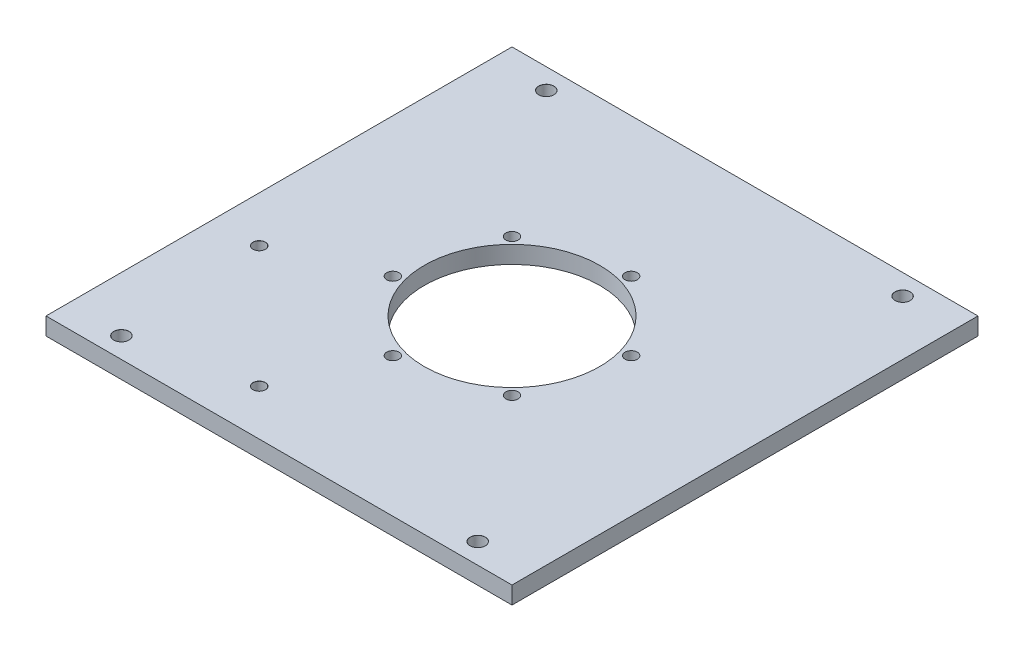
SolidWorks part; units mm, degrees
material "6061 Alloy"
ref_plane "Front Plane" through (0, 0, 0) normal (0, 0, 1) x (1, 0, 0)
ref_plane "Top Plane" through (0, 0, 0) normal (0, 1, 0) x (1, 0, 0)
ref_plane "Right Plane" through (0, 0, 0) normal (1, 0, 0) x (0, 0, -1)
sketch "Sketch1" plane through (0, 0, 0) normal (0, 1, 0) x (1, 0, 0)
  line L1 (-85, -85) -> (85, -85)
  line L2 (-85, -85) -> (-85, 85)
  line L3 (-85, 85) -> (85, 85)
  line L4 (85, -85) -> (85, 85)
  line L5 (-85, -85) -> (85, 85) construction
  line L6 (-85, 85) -> (85, -85) construction
  circle A1 centre (0, 0) radius 39.5
  arc A5 (-25.1023, 25.1023) -> (9.1881, 34.2904) centre (0, 0) cw
  arc A7 (9.1881, 34.2904) -> (-34.2904, -9.1881) centre (0, 0) ccw
  arc A9 (-34.2904, -9.1881) -> (-9.1881, -34.2904) centre (0, 0) ccw
  arc A11 (-9.1881, -34.2904) -> (25.1023, -25.1023) centre (0, 0) ccw
  circle A13 centre (0, 0) radius 32
  arc A14 (25.1023, -25.1023) -> (34.2904, 9.1881) centre (0, 0) ccw
extrude "Boss-Extrude3" add sketch "Sketch1" along normal blind 6.35
hole_wizard "M4 Clearance Hole2" positions "Sketch6" profile "Sketch7" hole size "M4" standard "ANSI Metric" end condition through all
sketch "Sketch6" plane through (0, 0, 0) normal (0, -1, 0) x (-1, 0, 0)
  point P0 (-9.1881, 34.2904)
  point P3 (25.1023, 25.1023)
  point P6 (34.2904, -9.1881)
  point P9 (9.1881, -34.2904)
  point P12 (-25.1023, -25.1023)
  point P15 (-34.2904, 9.1881)
sketch "Sketch7" plane through (9.1881, 0, -34.2904) normal (1, 0, 0) x (0, 0, -1)
  line L0 (0, 0) -> (0, 6.35)
  line L1 (0, 6.35) -> (2.25, 6.35)
  line L2 (2.25, 6.35) -> (2.25, 0.025)
  line L3 (2.25, 0.025) -> (2.275, 0)
  line L5 (2.275, 0) -> (0, 0)
  line L6 (-2.25, 0.025) -> (-2.275, 0) construction
  line L11 (0, -6.35) -> (0, 107.95) construction
  dimension "Thru Hole Dia." = 4.5
  dimension "Thru Hole Depth" = 6.35
  dimension "Near C'Sink Dia." = 4.55
  dimension "Near C'Sink Angle" = 90
sketch "Sketch13" plane through (0, 6.35, 0) normal (0, 1, 0) x (1, 0, 0)
  line L0 (-85, -85) -> (-46.1091, -46.1091)
  line L1 (-46.1091, -46.1091) -> (-68.3017, -23.9166)
  line L2 (-46.1091, -46.1091) -> (-23.9166, -68.3017)
hole_wizard "M4 Clearance Hole5" positions "Sketch14" profile "Sketch15" hole size "M4" standard "ANSI Metric" end condition through all
sketch "Sketch14" plane through (0, 6.35, 0) normal (0, 1, 0) x (1, 0, 0)
  point P0 (-68.3017, -23.9166)
  point P3 (-23.9166, -68.3017)
sketch "Sketch15" plane through (-68.3017, 6.35, 23.9166) normal (1, 0, 0) x (0, 0, 1)
  line L0 (0, 0) -> (0, 6.35)
  line L1 (0, 6.35) -> (2.25, 6.35)
  line L2 (2.25, 6.35) -> (2.25, 0.025)
  line L3 (2.25, 0.025) -> (2.275, 0)
  line L5 (2.275, 0) -> (0, 0)
  line L6 (-2.25, 0.025) -> (-2.275, 0) construction
  line L11 (0, -6.35) -> (0, 107.95) construction
  dimension "Thru Hole Dia." = 4.5
  dimension "Thru Hole Depth" = 6.35
  dimension "Near C'Sink Dia." = 4.55
  dimension "Near C'Sink Angle" = 90
sketch "Sketch16" plane through (0, 6.35, 0) normal (0, 1, 0) x (1, 0, 0)
  line L0 (-85, -85) -> (-55, -85)
  line L1 (-85, -85) -> (85, -85) construction
  line L2 (-55, -85) -> (-55, -70)
  line L3 (-85, -85) -> (-75, -85)
  line L4 (-75, -85) -> (-75, -70)
  line L5 (-75, -70) -> (-55, -70)
  line L6 (-85, 85) -> (-55, 85)
  line L7 (-85, 85) -> (85, 85) construction
  line L8 (85, 85) -> (55, 85)
  line L9 (85, -85) -> (55, -85)
  line L11 (-55, 85) -> (-75, 85)
  line L12 (-55, 85) -> (-55, 70)
  line L13 (-55, 70) -> (-75, 70)
  line L14 (-75, 85) -> (-75, 70)
  line L15 (55, 85) -> (75, 85)
  line L16 (55, 85) -> (55, 70)
  line L17 (55, 70) -> (75, 70)
  line L18 (75, 85) -> (75, 70)
  line L19 (55, -85) -> (75, -85)
  line L20 (55, -85) -> (55, -70)
  line L21 (55, -70) -> (75, -70)
  line L22 (75, -85) -> (75, -70)
hole_wizard "M5 Clearance Hole1" positions "Sketch19" profile "Sketch20" hole size "M5" standard "ANSI Metric" end condition through all
sketch "Sketch19" plane through (0, 6.35, 0) normal (0, 1, 0) x (1, 0, 0)
  point P0 (-65, -77.5)
sketch "Sketch20" plane through (-65, 6.35, 77.5) normal (1, 0, 0) x (0, 0, 1)
  line L0 (0, 0) -> (0, 6.35)
  line L1 (0, 6.35) -> (2.75, 6.35)
  line L2 (2.75, 6.35) -> (2.75, 0.025)
  line L3 (2.75, 0.025) -> (2.775, 0)
  line L5 (2.775, 0) -> (0, 0)
  line L6 (-2.75, 0.025) -> (-2.775, 0) construction
  line L11 (0, -6.35) -> (0, 107.95) construction
  dimension "Thru Hole Dia." = 5.5
  dimension "Thru Hole Depth" = 6.35
  dimension "Near C'Sink Dia." = 5.55
  dimension "Near C'Sink Angle" = 90
hole_wizard "M5 Clearance Hole2" positions "Sketch21" profile "Sketch22" hole size "M5" standard "ANSI Metric" end condition through all
sketch "Sketch21" plane through (0, 6.35, 0) normal (0, 1, 0) x (1, 0, 0)
  point P0 (-65, 77.5)
  point P2 (65, 77.5)
  point P4 (65, -77.5)
sketch "Sketch22" plane through (-65, 6.35, -77.5) normal (1, 0, 0) x (0, 0, 1)
  line L0 (0, 0) -> (0, 6.35)
  line L1 (0, 6.35) -> (2.75, 6.35)
  line L2 (2.75, 6.35) -> (2.75, 0.025)
  line L3 (2.75, 0.025) -> (2.775, 0)
  line L5 (2.775, 0) -> (0, 0)
  line L6 (-2.75, 0.025) -> (-2.775, 0) construction
  line L11 (0, -6.35) -> (0, 107.95) construction
  dimension "Thru Hole Dia." = 5.5
  dimension "Thru Hole Depth" = 6.35
  dimension "Near C'Sink Dia." = 5.55
  dimension "Near C'Sink Angle" = 90
